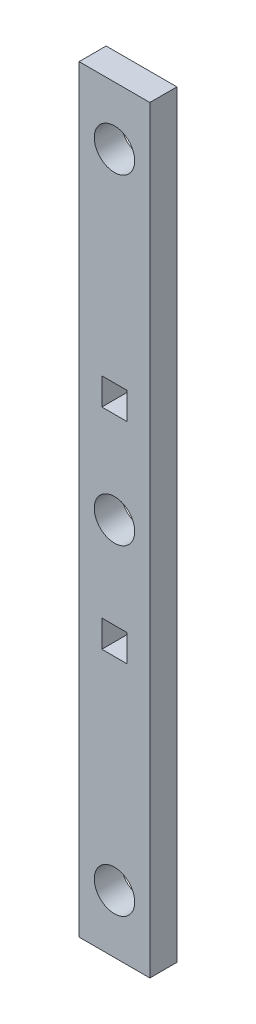
SolidWorks part; units mm, degrees
ref_plane "Front Plane" through (0, 0, 0) normal (0, 0, 1) x (1, 0, 0)
ref_plane "Top Plane" through (0, 0, 0) normal (0, 1, 0) x (1, 0, 0)
ref_plane "Right Plane" through (0, 0, 0) normal (1, 0, 0) x (0, 0, -1)
sketch "Model" plane through (0, 0, 0) normal (0, 0, 1) x (1, 0, 0)
  line L0 (7, 150) -> (7, 0) construction
  line L1 (0, 0) -> (14, 0)
  line L2 (0, 0) -> (0, 150)
  line L3 (0, 150) -> (14, 150)
  line L4 (14, 0) -> (14, 150)
  line L5 (0, 75) -> (14, 75) construction
  line L6 (4.5, 98.425) -> (9.5, 98.425)
  line L7 (4.5, 98.425) -> (4.5, 93.075)
  line L8 (4.5, 93.075) -> (9.5, 93.075)
  line L9 (9.5, 98.425) -> (9.5, 93.075)
  line L10 (4.5, 98.425) -> (9.5, 93.075) construction
  line L11 (4.5, 93.075) -> (9.5, 98.425) construction
  line L12 (4.5, 56.925) -> (9.5, 51.575) construction
  line L13 (4.5, 51.575) -> (9.5, 56.925) construction
  line L14 (9.5, 51.575) -> (9.5, 56.925)
  line L15 (4.5, 56.925) -> (9.5, 56.925)
  line L16 (4.5, 51.575) -> (4.5, 56.925)
  line L17 (4.5, 51.575) -> (9.5, 51.575)
  circle A0 centre (7, 138.5) radius 4
  circle A1 centre (7, 75) radius 4
  circle A5 centre (7, 11.5) radius 4
  point P18 (7, 95.75)
  point P29 (7, 54.25)
  dimension "D8" = 8
  dimension "D1" = 150
  dimension "D2" = 14
  dimension "D14" = 11.5
  dimension "D10" = 5.35
  dimension "D12" = 5
  dimension "D20" = 51.575
extrude "Boss-Extrude1" add sketch "Model" along normal blind 5.35
equation "\"mdfthick\"=5.35"
equation "\"D10@Model\"=\"mdfthick\""
equation "\"D1@Boss-Extrude1\"=\"mdfthick\""
